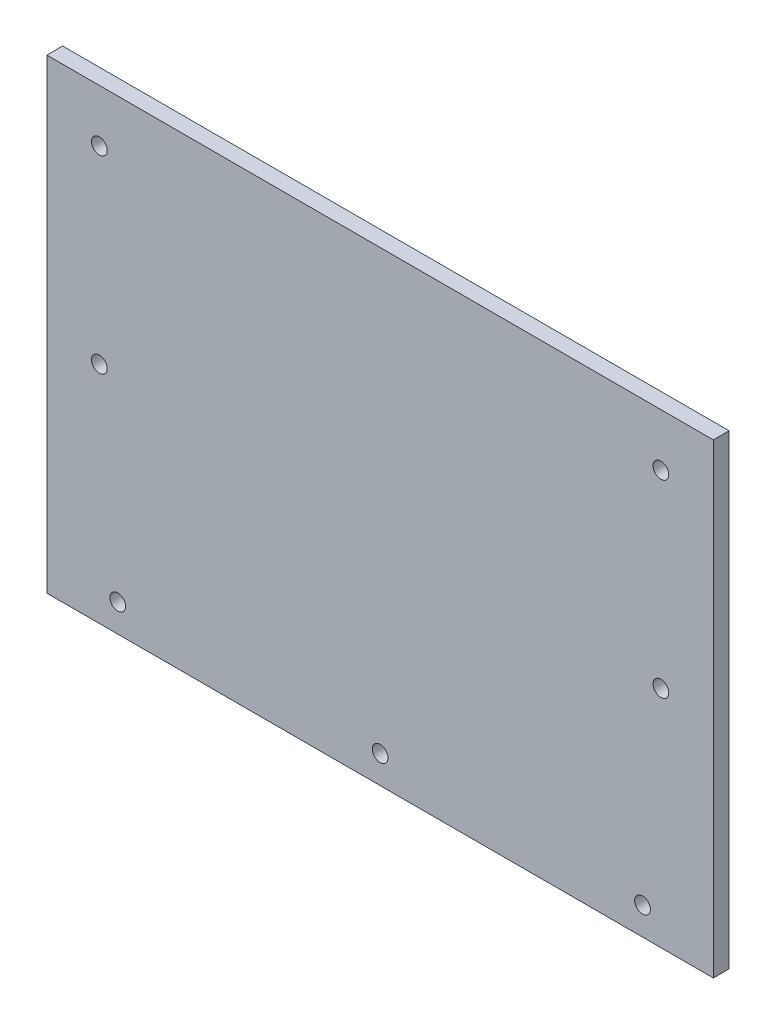
SolidWorks part; units mm, degrees
ref_plane "前视基准面" through (0, 0, 0) normal (0, 0, 1) x (1, 0, 0)
ref_plane "上视基准面" through (0, 0, 0) normal (0, 1, 0) x (1, 0, 0)
ref_plane "右视基准面" through (0, 0, 0) normal (1, 0, 0) x (0, 0, -1)
sketch "草图1" plane through (0, 0, 0) normal (0, 0, 1) x (1, 0, 0)
  line L1 (63.5, -46) -> (-63.5, -46)
  line L2 (63.5, -46) -> (63.5, 46)
  line L3 (63.5, 46) -> (-63.5, 46)
  line L4 (-63.5, -46) -> (-63.5, 46)
  line L5 (63.5, -46) -> (-63.5, 46) construction
  line L6 (63.5, 46) -> (-63.5, -46) construction
  point P0 (0, 0)
  dimension "D1" = 127
  dimension "D2" = 92
extrude "凸台-拉伸1" add sketch "草图1" along normal blind 3
sketch "草图2" plane through (0, 0, 3) normal (0, 0, 1) x (1, 0, 0)
  line L0 (-63.5, -46) -> (63.5, -46) construction
  line L1 (0, -46) -> (0, -37.5) construction
  line L2 (0, -37.5) -> (50, -37.5)
  line L3 (0, -37.5) -> (-50, -37.5)
  line L4 (-50, -37.5) -> (-16.0719, -37.5)
  circle A0 centre (0, -37.5) radius 1.5
  circle A1 centre (50, -37.5) radius 1.5
  circle A2 centre (-50, -37.5) radius 1.5
  dimension "D2" = 3
  dimension "D4" = 3
  dimension "D5" = 3
  dimension "D1" = 8.5
  dimension "D3" = 50
  dimension "D6" = 50
extrude "切除-拉伸1" cut sketch "草图2" against normal through all
sketch "草图3" plane through (0, 0, 3) normal (0, 0, 1) x (1, 0, 0)
  line L0 (0, 46) -> (0, 30.213) construction
  line L1 (-63.5, 46) -> (-53.5, 46)
  line L2 (-63.5, 46) -> (-63.5, 36)
  line L3 (-63.5, 36) -> (-53.5, 36)
  line L4 (-53.5, 46) -> (-53.5, 36)
  line L5 (63.5, 46) -> (-63.5, 46) construction
  line L6 (53.5, 46) -> (53.5, 36)
  line L7 (63.5, 36) -> (53.5, 36)
  line L8 (63.5, 46) -> (63.5, 36)
  line L9 (63.5, 46) -> (53.5, 46)
  line L10 (-63.5, 0) -> (-53.5, 0)
  line L11 (-63.5, 46) -> (-63.5, -46) construction
  circle A0 centre (-53.5, 36) radius 1.5
  circle A1 centre (53.5, 36) radius 1.5
  circle A2 centre (-53.5, 0) radius 1.5
  circle A3 centre (53.5, 0) radius 1.5
  dimension "D3" = 3
  dimension "D4" = 3
  dimension "D1" = 10
  dimension "D2" = 10
  dimension "D5" = 10
extrude "切除-拉伸2" cut sketch "草图3" against normal through all
sketch "草图4" plane through (0, 0, 0) normal (0, 0, -1) x (-1, 0, 0)
  line L0 (63.5, 46) -> (63.5, -46) construction
  line L1 (-63.5, -46) -> (63.5, -46)
  line L2 (-63.5, -46) -> (-63.5, -42.8)
  line L3 (-63.5, -42.8) -> (63.5, -42.8)
  line L4 (63.5, -46) -> (63.5, -42.8)
  dimension "D1" = 3.2
extrude "切除-拉伸3" cut sketch "草图4" against normal blind 10
